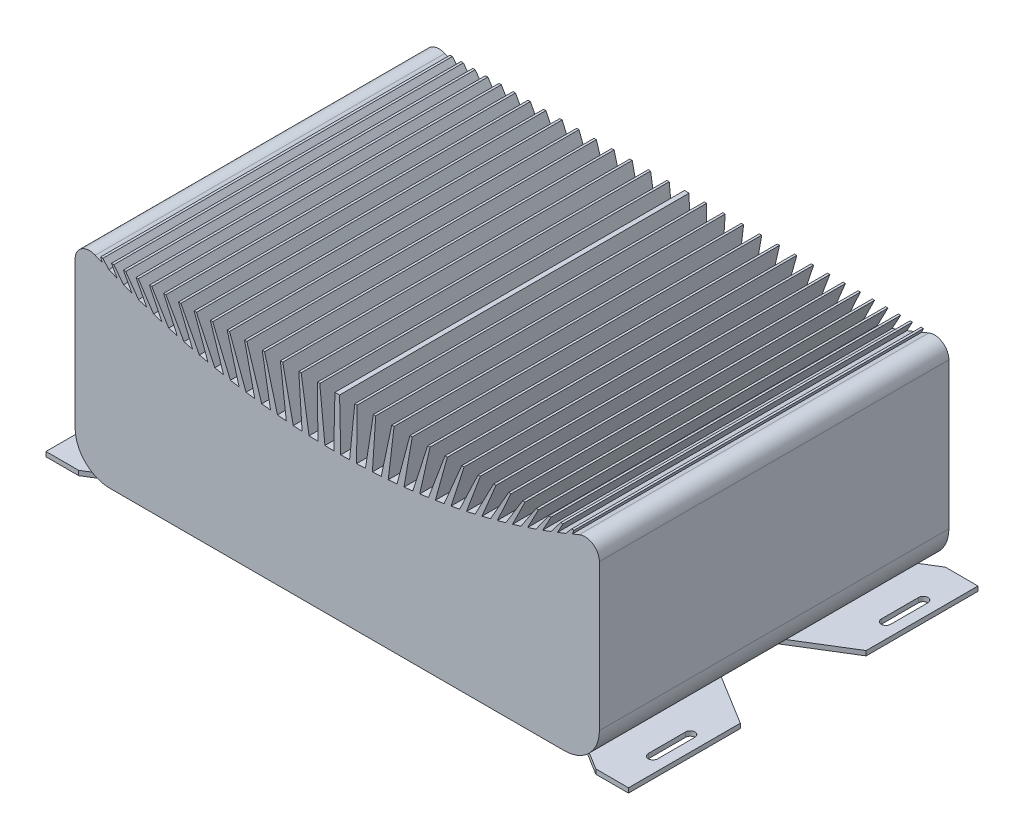
SolidWorks part; units mm, degrees
ref_plane "Plan de face" through (0, 0, 0) normal (0, 0, 1) x (1, 0, 0)
ref_plane "Plan de dessus" through (0, 0, 0) normal (0, 1, 0) x (1, 0, 0)
ref_plane "Plan de droite" through (0, 0, 0) normal (1, 0, 0) x (0, 0, -1)
sketch "Esquisse1" plane through (0, 0, 0) normal (0, 0, 1) x (1, 0, 0)
  line L0 (-112.5, 0) -> (112.5, 0)
  line L1 (112.5, 0) -> (112.5, 84) construction
  line L4 (0, 62) -> (0, 0) construction
  line L5 (0, 62) -> (72.7353, 62) construction
  line L6 (112.5, 84) -> (0, 84) construction
  line L7 (0, 84) -> (0, 62) construction
  line L8 (112.5, 77.8033) -> (112.5, 0)
  line L9 (-1, 84) -> (1, 84)
  line L10 (1, 84) -> (1.5, 62.0043)
  line L11 (1.5, 62.0043) -> (5.2997, 62.0537)
  line L12 (5.2997, 62.0537) -> (7.5192, 84)
  line L13 (7.5192, 84) -> (8.5192, 84)
  line L14 (8.5192, 84) -> (8.2987, 62.1316)
  line L15 (8.2987, 62.1316) -> (12.0958, 62.2798)
  line L16 (12.0958, 62.2798) -> (15.4982, 84)
  line L17 (15.4982, 84) -> (16.4982, 84)
  line L18 (16.4982, 84) -> (15.0917, 62.4356)
  line L19 (15.0917, 62.4356) -> (18.8837, 62.6824)
  line L20 (18.8837, 62.6824) -> (23.3975, 84)
  line L21 (23.3975, 84) -> (24.3975, 84)
  line L22 (24.3975, 84) -> (21.8746, 62.9161)
  line L23 (21.8746, 62.9161) -> (25.6589, 63.2613)
  line L24 (25.6589, 63.2613) -> (31.1789, 84)
  line L25 (31.1789, 84) -> (32.1789, 84)
  line L26 (32.1789, 84) -> (28.6427, 63.5726)
  line L27 (28.6427, 63.5726) -> (32.4167, 64.016)
  line L28 (32.4167, 64.016) -> (38.8058, 84)
  line L29 (38.8058, 84) -> (39.8058, 84)
  line L30 (39.8058, 84) -> (35.3914, 64.4048)
  line L31 (35.3914, 64.4048) -> (39.1527, 64.9462)
  line L32 (39.1527, 64.9462) -> (46.2439, 84)
  line L33 (46.2439, 84) -> (47.2439, 84)
  line L34 (47.2439, 84) -> (42.1163, 65.4121)
  line L35 (42.1163, 65.4121) -> (45.8622, 66.051)
  line L36 (45.8622, 66.051) -> (53.4618, 84)
  line L37 (53.4618, 84) -> (54.4618, 84)
  line L38 (54.4618, 84) -> (48.8126, 66.5938)
  line L40 (0, 84) -> (0, 62) construction
  line L41 (5.2997, 62.0537) -> (8.2987, 62.1316) construction
  line L42 (12.0958, 62.2798) -> (15.0917, 62.4356) construction
  line L43 (18.8837, 62.6824) -> (21.8746, 62.9161) construction
  line L44 (25.6589, 63.2613) -> (28.6427, 63.5726) construction
  line L45 (32.4167, 64.016) -> (35.3914, 64.4048) construction
  line L46 (39.1527, 64.9462) -> (42.1163, 65.4121) construction
  line L47 (45.8622, 66.051) -> (48.8126, 66.5938) construction
  line L48 (8.0192, 84) -> (6.7992, 62.0927) construction
  line L49 (6.7992, 62.0927) -> (13.5938, 62.3577) construction
  line L50 (13.5938, 62.3577) -> (15.9982, 84) construction
  line L51 (15.9982, 84) -> (23.8975, 84) construction
  line L52 (23.8975, 84) -> (20.3791, 62.7992) construction
  line L53 (27.1508, 63.4169) -> (31.6789, 84) construction
  line L54 (39.3058, 84) -> (33.9041, 64.2104) construction
  line L55 (40.6345, 65.1791) -> (46.7439, 84) construction
  line L56 (53.9618, 84) -> (47.3374, 66.3224) construction
  line L57 (0, 0) -> (0, -60) construction
  line L58 (48.8126, 66.5938) -> (52.5407, 67.3299)
  line L59 (52.5407, 67.3299) -> (60.431, 84)
  line L60 (60.431, 84) -> (61.431, 84)
  line L61 (61.431, 84) -> (55.4761, 67.9492)
  line L62 (55.4761, 67.9492) -> (59.1837, 68.7819)
  line L63 (59.1837, 68.7819) -> (67.1264, 84)
  line L64 (67.1264, 84) -> (68.1264, 84)
  line L65 (68.1264, 84) -> (62.102, 69.4773)
  line L66 (62.102, 69.4773) -> (65.7867, 70.4061)
  line L67 (65.7867, 70.4061) -> (73.5265, 84)
  line L68 (73.5265, 84) -> (74.5265, 84)
  line L69 (74.5265, 84) -> (68.686, 71.177)
  line L70 (68.686, 71.177) -> (72.3453, 72.2013)
  line L71 (72.3453, 72.2013) -> (79.6132, 84)
  line L72 (79.6132, 84) -> (80.6132, 84)
  line L73 (80.6132, 84) -> (75.2236, 73.0473)
  line L74 (75.2236, 73.0473) -> (78.8551, 74.1663)
  line L75 (78.8551, 74.1663) -> (85.3724, 84)
  line L76 (85.3724, 84) -> (86.3724, 84)
  line L77 (86.3724, 84) -> (81.7103, 75.0869)
  line L79 (52.5407, 67.3299) -> (55.4761, 67.9492) construction
  line L80 (59.1837, 68.7819) -> (62.102, 69.4773) construction
  line L81 (65.7867, 70.4061) -> (68.686, 71.177) construction
  line L82 (72.3453, 72.2013) -> (75.2236, 73.0473) construction
  line L83 (78.8551, 74.1663) -> (81.7103, 75.0869) construction
  line L84 (54.0084, 67.6396) -> (60.931, 84) construction
  line L85 (60.931, 84) -> (67.6264, 84) construction
  line L86 (67.6264, 84) -> (60.6428, 69.1296) construction
  line L87 (81.7103, 75.0869) -> (85.3116, 76.2999)
  line L88 (67.2364, 70.7916) -> (74.0265, 84) construction
  line L89 (74.0265, 84) -> (80.1132, 84) construction
  line L90 (80.1132, 84) -> (73.7845, 72.6243) construction
  line L91 (73.7845, 72.6243) -> (80.2827, 74.6266) construction
  line L92 (80.2827, 74.6266) -> (85.8724, 84) construction
  line L93 (85.3116, 76.2999) -> (90.7932, 84)
  line L94 (90.7932, 84) -> (91.7932, 84)
  line L95 (91.7932, 84) -> (88.1419, 77.2943)
  line L96 (88.1419, 77.2943) -> (91.7104, 78.6005)
  line L97 (91.7104, 78.6005) -> (95.8684, 84)
  line L98 (95.8684, 84) -> (96.8684, 84)
  line L99 (96.8684, 84) -> (94.514, 79.6682)
  line L100 (94.514, 79.6682) -> (98.0473, 81.0666)
  line L101 (98.0473, 81.0666) -> (100.5938, 84)
  line L102 (100.5938, 84) -> (101.5938, 84)
  line L103 (101.5938, 84) -> (100.8222, 82.2068)
  line L104 (100.8222, 82.2068) -> (103.8437, 83.491)
  line L105 (85.3116, 76.2999) -> (88.1419, 77.2943) construction
  line L106 (91.7104, 78.6005) -> (94.514, 79.6682) construction
  line L107 (98.0473, 81.0666) -> (100.8222, 82.2068) construction
  line L108 (91.2932, 84) -> (86.7267, 76.7971) construction
  line L109 (93.1122, 79.1343) -> (96.3684, 84) construction
  line L110 (101.0938, 84) -> (99.4347, 81.6367) construction
  line L111 (-112.5, 77.8033) -> (-112.5, 0)
  line L112 (-100.8222, 82.2068) -> (-103.8437, 83.491)
  line L113 (-101.5938, 84) -> (-100.8222, 82.2068)
  line L114 (-100.5938, 84) -> (-101.5938, 84)
  line L115 (-98.0473, 81.0666) -> (-100.5938, 84)
  line L116 (-94.514, 79.6682) -> (-98.0473, 81.0666)
  line L117 (-96.8684, 84) -> (-94.514, 79.6682)
  line L118 (-95.8684, 84) -> (-96.8684, 84)
  line L119 (-91.7104, 78.6005) -> (-95.8684, 84)
  line L120 (-88.1419, 77.2943) -> (-91.7104, 78.6005)
  line L121 (-91.7932, 84) -> (-88.1419, 77.2943)
  line L122 (-90.7932, 84) -> (-91.7932, 84)
  line L123 (-85.3116, 76.2999) -> (-90.7932, 84)
  line L124 (-81.7103, 75.0869) -> (-85.3116, 76.2999)
  line L125 (-86.3724, 84) -> (-81.7103, 75.0869)
  line L126 (-85.3724, 84) -> (-86.3724, 84)
  line L127 (-78.8551, 74.1663) -> (-85.3724, 84)
  line L128 (-75.2236, 73.0473) -> (-78.8551, 74.1663)
  line L129 (-80.6132, 84) -> (-75.2236, 73.0473)
  line L130 (-79.6132, 84) -> (-80.6132, 84)
  line L131 (-72.3453, 72.2013) -> (-79.6132, 84)
  line L132 (-68.686, 71.177) -> (-72.3453, 72.2013)
  line L133 (-74.5265, 84) -> (-68.686, 71.177)
  line L134 (-73.5265, 84) -> (-74.5265, 84)
  line L135 (-65.7867, 70.4061) -> (-73.5265, 84)
  line L136 (-62.102, 69.4773) -> (-65.7867, 70.4061)
  line L137 (-68.1264, 84) -> (-62.102, 69.4773)
  line L138 (-67.1264, 84) -> (-68.1264, 84)
  line L139 (-59.1837, 68.7819) -> (-67.1264, 84)
  line L140 (-55.4761, 67.9492) -> (-59.1837, 68.7819)
  line L141 (-61.431, 84) -> (-55.4761, 67.9492)
  line L142 (-60.431, 84) -> (-61.431, 84)
  line L143 (-52.5407, 67.3299) -> (-60.431, 84)
  line L144 (-48.8126, 66.5938) -> (-52.5407, 67.3299)
  line L145 (-54.4618, 84) -> (-48.8126, 66.5938)
  line L146 (-53.4618, 84) -> (-54.4618, 84)
  line L147 (-45.8622, 66.051) -> (-53.4618, 84)
  line L148 (-42.1163, 65.4121) -> (-45.8622, 66.051)
  line L149 (-47.2439, 84) -> (-42.1163, 65.4121)
  line L150 (-46.2439, 84) -> (-47.2439, 84)
  line L151 (-39.1527, 64.9462) -> (-46.2439, 84)
  line L152 (-35.3914, 64.4048) -> (-39.1527, 64.9462)
  line L153 (-39.8058, 84) -> (-35.3914, 64.4048)
  line L154 (-38.8058, 84) -> (-39.8058, 84)
  line L155 (-32.4167, 64.016) -> (-38.8058, 84)
  line L156 (-28.6427, 63.5726) -> (-32.4167, 64.016)
  line L157 (-32.1789, 84) -> (-28.6427, 63.5726)
  line L158 (-31.1789, 84) -> (-32.1789, 84)
  line L159 (-25.6589, 63.2613) -> (-31.1789, 84)
  line L160 (-21.8746, 62.9161) -> (-25.6589, 63.2613)
  line L161 (-24.3975, 84) -> (-21.8746, 62.9161)
  line L162 (-23.3975, 84) -> (-24.3975, 84)
  line L163 (-18.8837, 62.6824) -> (-23.3975, 84)
  line L164 (-15.0917, 62.4356) -> (-18.8837, 62.6824)
  line L165 (-16.4982, 84) -> (-15.0917, 62.4356)
  line L166 (-15.4982, 84) -> (-16.4982, 84)
  line L167 (-12.0958, 62.2798) -> (-15.4982, 84)
  line L168 (-8.2987, 62.1316) -> (-12.0958, 62.2798)
  line L169 (-8.5192, 84) -> (-8.2987, 62.1316)
  line L170 (-7.5192, 84) -> (-8.5192, 84)
  line L171 (-5.2997, 62.0537) -> (-7.5192, 84)
  line L172 (-1.5, 62.0043) -> (-5.2997, 62.0537)
  line L173 (-1, 84) -> (-1.5, 62.0043)
  arc A0 (0, 62) -> (103.8437, 83.491) centre (0, 323.6301) ccw construction
  arc A1 (103.8437, 83.491) -> (112.5, 77.8033) centre (106.3033, 77.8033) cw
  arc A2 (-103.8437, 83.491) -> (-112.5, 77.8033) centre (-106.3033, 77.8033) ccw
  dimension "D8" = 22
  dimension "D1" = 112.5
  dimension "D2" = 1
  dimension "D3" = 1.5
  dimension "D4" = 60
  dimension "D5" = 1
  dimension "D6" = 3
  dimension "D7" = 84
  dimension "D9" = 3.8
extrude "Boss.-Extru.1" add sketch "Esquisse1" along normal blind 150
fillet "Congé1" radius 15 2 edges at (-112.5, 0, 75) (112.5, 0, 75)
sketch "Esquisse2" plane through (0, 0, 0) normal (0, -1, 0) x (1, 0, 0)
  line L0 (85, 134) -> (111, 150)
  line L1 (112.5, 150) -> (97.5, 150) construction
  line L2 (111, 150) -> (125, 150)
  line L3 (125, 150) -> (125, 102)
  line L4 (125, 102) -> (99, 86)
  line L5 (99, 86) -> (99, 64)
  line L6 (99, 64) -> (125, 48)
  line L7 (125, 48) -> (125, 0)
  line L8 (125, 0) -> (111, 0)
  line L9 (97.5, 0) -> (112.5, 0) construction
  line L10 (111, 0) -> (85, 16)
  line L11 (85, 16) -> (85, 34.7483)
  line L12 (85, 34.7483) -> (85, 134)
  line L13 (-97.5, 75) -> (97.5, 75) construction
  line L14 (-97.5, 150) -> (-97.5, 0) construction
  line L15 (97.5, 0) -> (97.5, 150) construction
  line L16 (118.5, 133) -> (118.5, 117) construction
  line L17 (120.5, 133) -> (120.5, 117)
  line L18 (116.5, 133) -> (116.5, 117)
  line L19 (118.5, 17) -> (118.5, 33) construction
  line L20 (120.5, 17) -> (120.5, 33)
  line L21 (116.5, 17) -> (116.5, 33)
  line L22 (0, 0) -> (0, 150) construction
  line L23 (-97.5, 150) -> (97.5, 150) construction
  line L24 (-118.5, 133) -> (-118.5, 117) construction
  line L25 (-120.5, 133) -> (-120.5, 117)
  line L26 (-116.5, 133) -> (-116.5, 117)
  line L27 (-118.5, 17) -> (-118.5, 33) construction
  line L28 (-120.5, 17) -> (-120.5, 33)
  line L29 (-116.5, 17) -> (-116.5, 33)
  line L30 (-85, 34.7483) -> (-85, 134)
  line L31 (-85, 16) -> (-85, 34.7483)
  line L32 (-111, 0) -> (-85, 16)
  line L33 (-125, 0) -> (-111, 0)
  line L34 (-125, 48) -> (-125, 0)
  line L35 (-99, 64) -> (-125, 48)
  line L36 (-99, 86) -> (-99, 64)
  line L37 (-125, 102) -> (-99, 86)
  line L38 (-125, 150) -> (-125, 102)
  line L39 (-111, 150) -> (-125, 150)
  line L40 (-85, 134) -> (-111, 150)
  arc A0 (120.5, 133) -> (116.5, 133) centre (118.5, 133) ccw
  arc A1 (116.5, 117) -> (120.5, 117) centre (118.5, 117) ccw
  arc A2 (120.5, 17) -> (116.5, 17) centre (118.5, 17) cw
  arc A3 (116.5, 33) -> (120.5, 33) centre (118.5, 33) cw
  arc A4 (-120.5, 133) -> (-116.5, 133) centre (-118.5, 133) cw
  arc A5 (-116.5, 117) -> (-120.5, 117) centre (-118.5, 117) cw
  arc A6 (-120.5, 17) -> (-116.5, 17) centre (-118.5, 17) ccw
  arc A7 (-116.5, 33) -> (-120.5, 33) centre (-118.5, 33) ccw
  point P22 (118.5, 125)
  point P31 (118.5, 25)
  point P36 (118.5, 135)
  point P37 (118.5, 15)
  point P38 (118.5, 115)
  point P46 (-118.5, 125)
  point P53 (-118.5, 25)
  dimension "D1" = 2
  dimension "D2" = 120
  dimension "D3" = 20
  dimension "D4" = 250
  dimension "D5" = 237
  dimension "D6" = 14
  dimension "D7" = 40
  dimension "D8" = 16
  dimension "D9" = 54
  dimension "D10" = 14
extrude "Boss.-Extru.2" add sketch "Esquisse2" along normal blind 2
